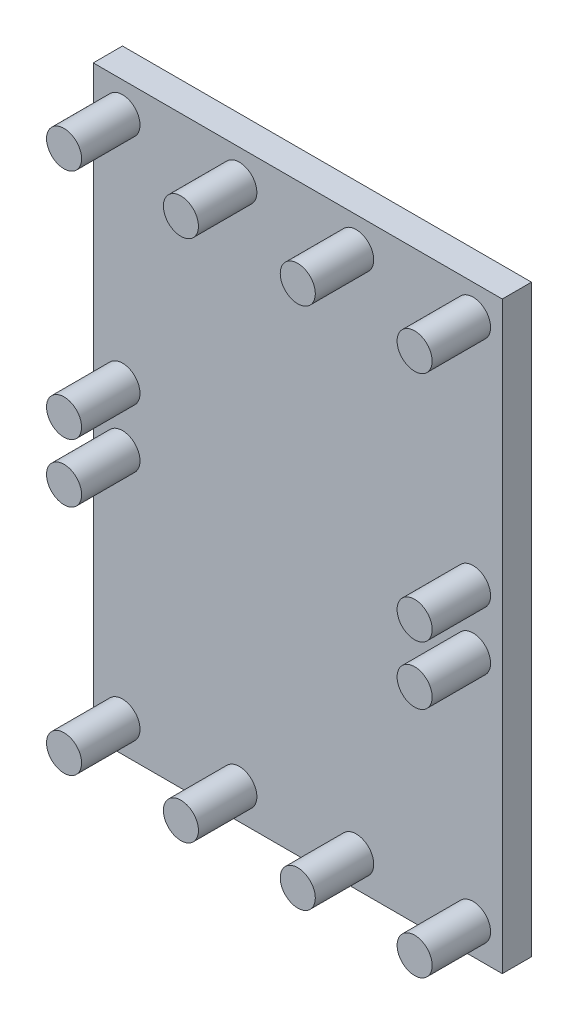
SolidWorks part; units mm, degrees
ref_plane "Front Plane" through (0, 0, 0) normal (1, 0, 0) x (0, 1, 0)
ref_plane "Top Plane" through (0, 0, 0) normal (0, 0, 1) x (0, 1, 0)
ref_plane "Right Plane" through (0, 0, 0) normal (0, 1, 0) x (-1, 0, 0)
sketch "Sketch1" plane through (0, 0, 0) normal (0, 0, 1) x (0, 1, 0)
  line L0 (0, 0) -> (80, 0)
  line L1 (80, 0) -> (80, 56)
  line L2 (80, 56) -> (0, 56)
  line L3 (0, 56) -> (0, 0)
extrude "Boss-Extrude1" add sketch "Sketch1" along normal blind 4
sketch "Sketch2" plane through (0, 0, 4) normal (0, 0, 1) x (1, 0, 0)
  circle A0 centre (-4, 4.1722) radius 2.4
  circle A2 centre (-20, 4.1722) radius 2.4
  circle A4 centre (-36, 4.1722) radius 2.4
  circle A6 centre (-52, 4.1722) radius 2.4
  circle A7 centre (-52, 75.8278) radius 2.4
  circle A8 centre (-36, 75.8278) radius 2.4
  circle A9 centre (-20, 75.8278) radius 2.4
  circle A10 centre (-4, 75.8278) radius 2.4
  circle A11 centre (-4, 36) radius 2.4
  circle A12 centre (-4, 44) radius 2.4
  circle A13 centre (-52, 44) radius 2.4
  circle A14 centre (-52, 36) radius 2.4
extrude "Boss-Extrude2" add sketch "Sketch2" along normal blind 8
